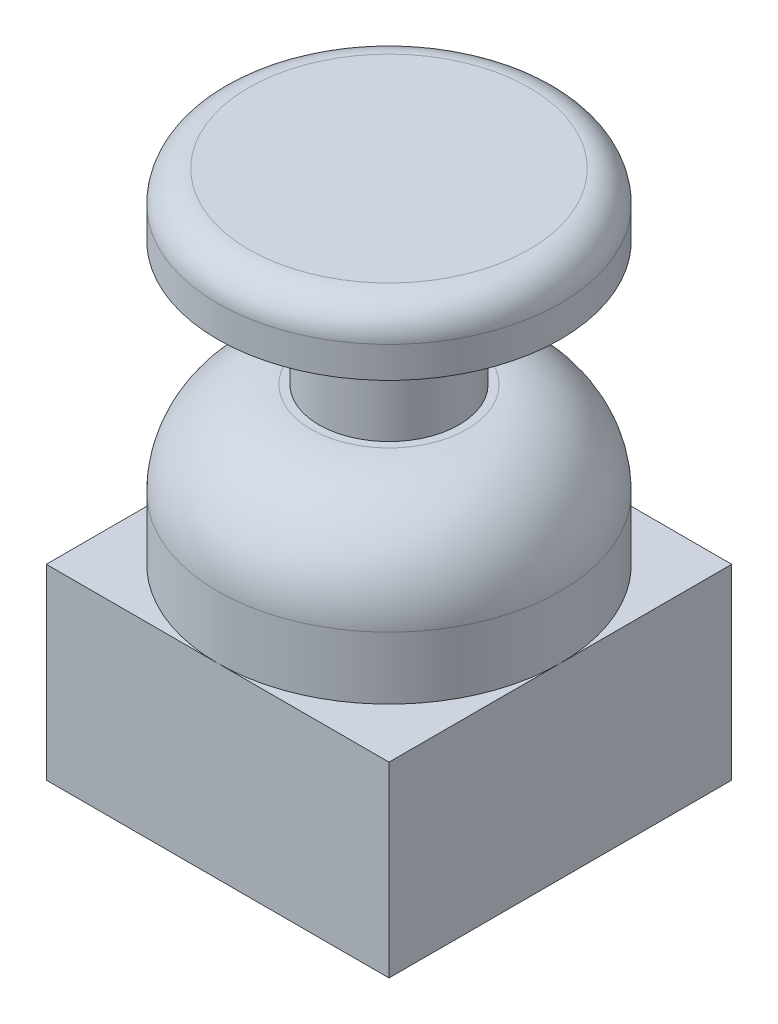
SolidWorks part; units mm, degrees
ref_plane "Front Plane" through (0, 0, 0) normal (0, 0, 1) x (1, 0, 0)
ref_plane "Top Plane" through (0, 0, 0) normal (0, 1, 0) x (1, 0, 0)
ref_plane "Right Plane" through (0, 0, 0) normal (1, 0, 0) x (0, 0, -1)
sketch "Sketch1" plane through (0, 0, 0) normal (0, 0, 1) x (1, 0, 0)
  line L0 (0, 0) -> (-11, 0)
  line L1 (-11, 0) -> (-11, 16)
  line L2 (-5, 22) -> (-4.5, 22)
  line L3 (-4.5, 22) -> (-4.5, 30)
  line L4 (-4.5, 30) -> (-11, 30)
  line L5 (-11, 30) -> (-11, 32)
  line L6 (-9, 34) -> (0, 34)
  line L7 (0, 34) -> (0, 0)
  arc A0 (-11, 32) -> (-9, 34) centre (-9, 32) cw
  arc A1 (-11, 16) -> (-5, 22) centre (-5, 16) cw
  point P11 (-11, 34)
  point P14 (-11, 22)
  dimension "D7" = 2
  dimension "D8" = 6
  dimension "D1" = 22
  dimension "D2" = 8
  dimension "D3" = 4
  dimension "D4" = 4.5
  dimension "D5" = 11
  dimension "D6" = 11
revolve "Revolve1" add sketch "Sketch1" angle 360 about L7
sketch "Sketch2" plane through (0, 0, 0) normal (0, -1, 0) x (1, 0, 0)
  line L1 (-11, -11) -> (11, -11)
  line L2 (-11, -11) -> (-11, 11)
  line L3 (-11, 11) -> (11, 11)
  line L4 (11, -11) -> (11, 11)
  line L5 (-11, -11) -> (11, 11) construction
  line L6 (-11, 11) -> (11, -11) construction
  circle A0 centre (0, 0) radius 11 construction
  point P0 (0, 0)
extrude "Boss-Extrude1" add sketch "Sketch2" against normal blind 12
